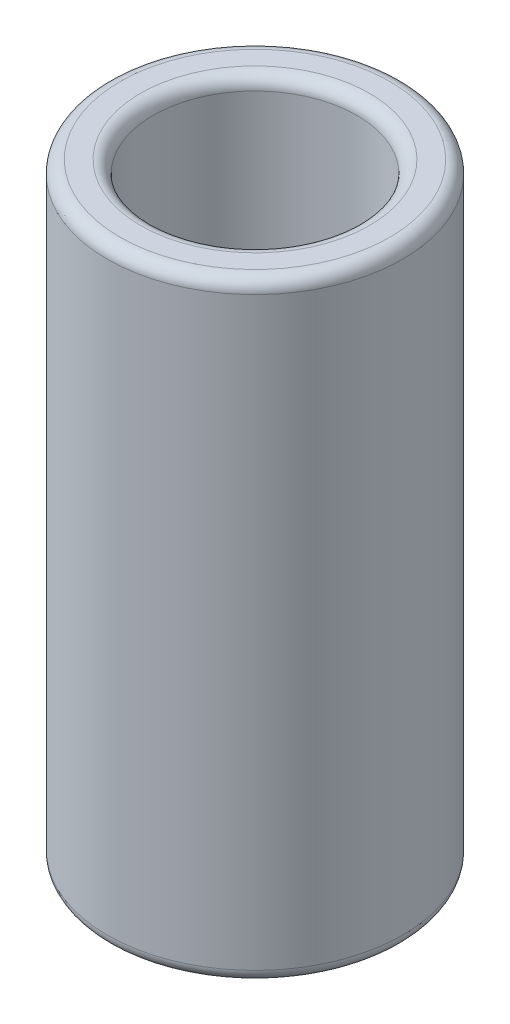
SolidWorks part; units mm, degrees
material "6061-T6 (SS)"
ref_plane "Front Plane" through (0, 0, 0) normal (0, 0, 1) x (1, 0, 0)
ref_plane "Top Plane" through (0, 0, 0) normal (0, 1, 0) x (1, 0, 0)
ref_plane "Right Plane" through (0, 0, 0) normal (1, 0, 0) x (0, 0, -1)
sketch "Sketch1" plane through (0, 0, 0) normal (0, 1, 0) x (1, 0, 0)
  circle A0 centre (0, 0) radius 5.8
  circle A1 centre (0, 0) radius 4
  dimension "D1" = 11.6
  dimension "D2" = 8
extrude "Boss-Extrude1" add sketch "Sketch1" along normal blind 24
fillet "Fillet1" radius 0.5 2 edges at (0, 0, 5.8) (0, 24, 5.8)
fillet "Fillet2" radius 0.5 2 edges at (0, 0, 4) (0, 24, 4)
